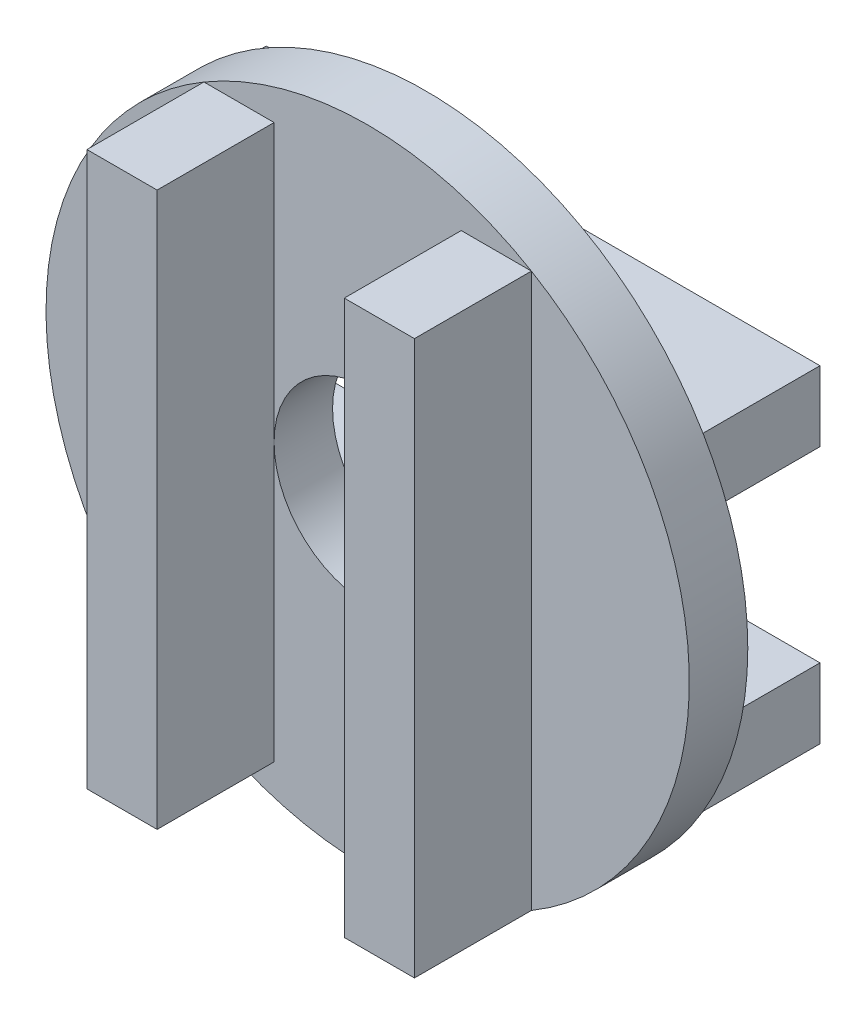
SolidWorks part; units mm, degrees
ref_plane "Płaszczyzna przednia" through (0, 0, 0) normal (0, 0, 1) x (1, 0, 0)
ref_plane "Płaszczyzna górna" through (0, 0, 0) normal (0, 1, 0) x (1, 0, 0)
ref_plane "Płaszczyzna prawa" through (0, 0, 0) normal (1, 0, 0) x (0, 0, -1)
sketch "Szkic1" plane through (0, 0, 0) normal (0, 0, 1) x (1, 0, 0)
  circle A0 centre (0, 0) radius 16
  circle A1 centre (0, 0) radius 55
  dimension "D1" = 32
  dimension "D2" = 110
extrude "Dodanie-wyciągnięcie1" add sketch "Szkic1" along normal blind 10
sketch "Szkic2" plane through (0, 0, 10) normal (0, 0, 1) x (1, 0, 0)
  line L0 (0, 0) -> (0, 55) construction
  line L1 (-16, -47.3392) -> (-28, -47.3392)
  line L2 (16, 47.3392) -> (28, 47.3392)
  line L3 (16, 47.3392) -> (16, -47.3392)
  line L4 (16, -47.3392) -> (28, -47.3392)
  line L5 (28, 47.3392) -> (28, -47.3392)
  line L6 (-28, 47.3392) -> (-28, -47.3392)
  line L7 (-16, 47.3392) -> (-28, 47.3392)
  line L8 (-16, 47.3392) -> (-16, -47.3392)
  circle A0 centre (0, 0) radius 55 construction
  circle A1 centre (0, 0) radius 16 construction
  point P12 (0, 0)
  point P13 (0, 0)
  dimension "D1" = 12
extrude "Dodanie-wyciągnięcie2" add sketch "Szkic2" along normal blind 20
sketch "Szkic3" plane through (0, 0, 0) normal (0, 0, -1) x (-1, 0, 0)
  line L0 (0, 0) -> (-55, 0) construction
  line L1 (-47.3392, -16) -> (47.3392, -16)
  line L2 (-47.3392, 28) -> (47.3392, 28)
  line L3 (-47.3392, 28) -> (-47.3392, 16)
  line L4 (-47.3392, 16) -> (47.3392, 16)
  line L5 (47.3392, 28) -> (47.3392, 16)
  line L6 (47.3392, -28) -> (47.3392, -16)
  line L7 (-47.3392, -28) -> (47.3392, -28)
  line L8 (-47.3392, -28) -> (-47.3392, -16)
  circle A0 centre (0, 0) radius 55 construction
  circle A1 centre (0, 0) radius 16 construction
  point P11 (0, 0)
  point P12 (0, 0)
  dimension "D1" = 12
extrude "Dodanie-wyciągnięcie3" add sketch "Szkic3" along normal blind 20
